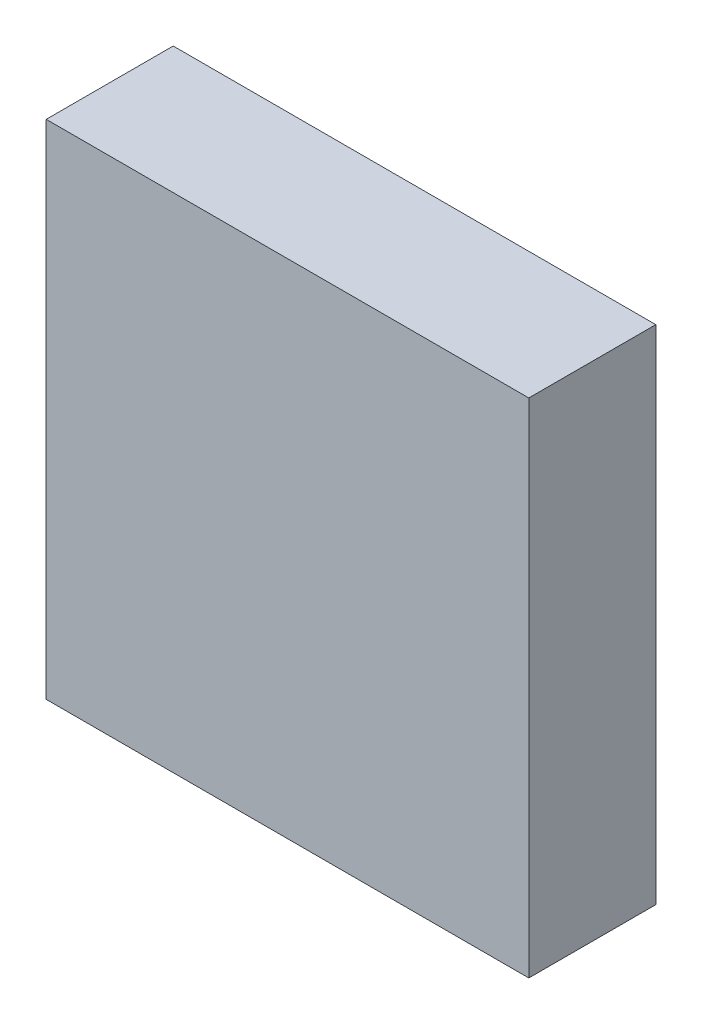
SolidWorks part; units mm, degrees
ref_plane "正面" through (0, 0, 0) normal (0, 0, 1) x (1, 0, 0)
ref_plane "平面" through (0, 0, 0) normal (0, 1, 0) x (1, 0, 0)
ref_plane "右側面" through (0, 0, 0) normal (1, 0, 0) x (0, 0, -1)
sketch "ｽｹｯﾁ1" plane through (0, 0, 0) normal (0, 1, 0) x (1, 0, 0)
  line L1 (0, 0) -> (1710, 0)
  line L2 (0, 0) -> (0, 450)
  line L3 (0, 450) -> (1710, 450)
  line L4 (1710, 0) -> (1710, 450)
  dimension "D1" = 1710
  dimension "D2" = 450
extrude "ﾎﾞｽ - 押し出し1" add sketch "ｽｹｯﾁ1" along normal blind 1780
